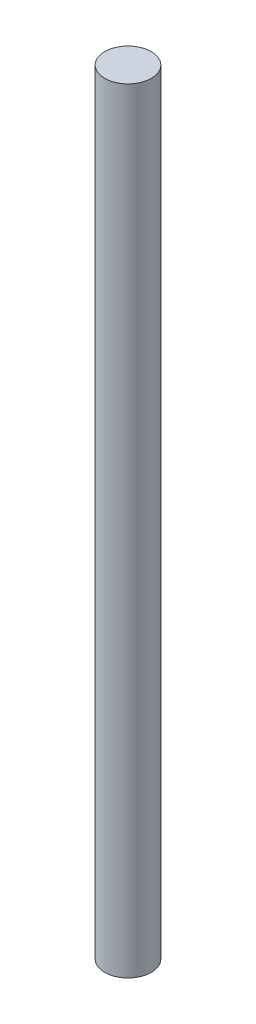
SolidWorks part; units mm, degrees
ref_plane "Ebene vorne" through (0, 0, 0) normal (0, 0, 1) x (1, 0, 0)
ref_plane "Ebene oben" through (0, 0, 0) normal (0, 1, 0) x (1, 0, 0)
ref_plane "Ebene rechts" through (0, 0, 0) normal (1, 0, 0) x (0, 0, -1)
sketch "Skizze2" plane through (0, 0, 0) normal (0, 1, 0) x (1, 0, 0)
  circle A0 centre (0, 0) radius 3
  dimension "D1" = 6
extrude "Aufsatz-Linear austragen1" add sketch "Skizze2" along normal blind 100
sketch "Skizze3" plane through (0, 0, 0) normal (0, -1, 0) x (-1, 0, 0)
  circle A0 centre (0, 0) radius 1.65
  point P3 (0, 0)
extrude "Schnitt-Linear austragen1" cut sketch "Skizze3" against normal blind 4 contours A0
